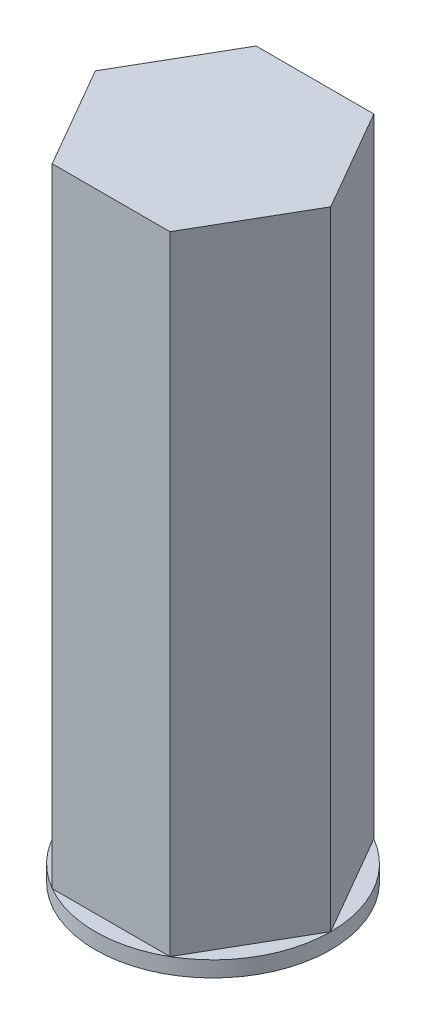
SolidWorks part; units mm, degrees
ref_plane "Front Plane" through (0, 0, 0) normal (0, 0, 1) x (1, 0, 0)
ref_plane "Top Plane" through (0, 0, 0) normal (0, 1, 0) x (1, 0, 0)
ref_plane "Right Plane" through (0, 0, 0) normal (1, 0, 0) x (0, 0, -1)
sketch "Sketch1" plane through (0, 0, 0) normal (0, 1, 0) x (1, 0, 0)
  circle A0 centre (0, 0) radius 7.5
extrude "Boss-Extrude1" add sketch "Sketch1" along normal blind 1
sketch "Sketch2" plane through (0, 1, 0) normal (0, 1, 0) x (1, 0, 0)
  line L1 (7.5, 0) -> (3.75, 6.4952)
  line L2 (3.75, 6.4952) -> (-3.75, 6.4952)
  line L3 (-3.75, 6.4952) -> (-7.5, 0)
  line L4 (-7.5, 0) -> (-3.75, -6.4952)
  line L5 (-3.75, -6.4952) -> (3.75, -6.4952)
  line L6 (3.75, -6.4952) -> (7.5, 0)
  circle A0 centre (0, 0) radius 6.4952 construction
extrude "Boss-Extrude2" add sketch "Sketch2" along normal blind 40
